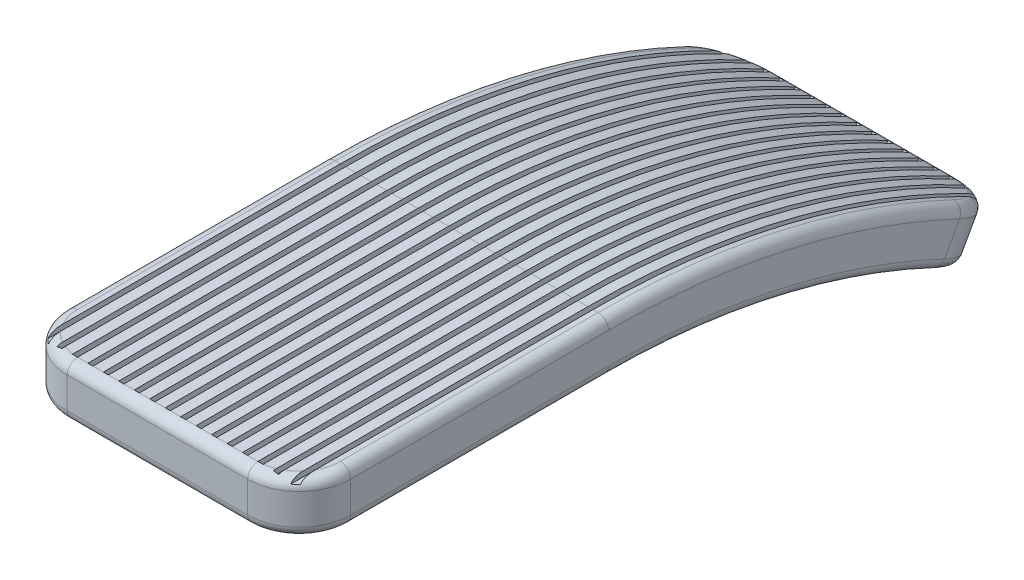
SolidWorks part; units mm, degrees
material "Silicon Rubber"
ref_plane "Front" through (0, 0, 0) normal (0, 0, 1) x (1, 0, 0)
ref_plane "Top" through (0, 0, 0) normal (0, 1, 0) x (1, 0, 0)
ref_plane "Right" through (0, 0, 0) normal (1, 0, 0) x (0, 0, -1)
sketch "Sketch1" plane through (0, 0, 0) normal (1, 0, 0) x (0, 0, -1)
  line L0 (0, 0) -> (-60, 0)
  line L1 (0, 10) -> (-60, 10)
  line L2 (-60, 10) -> (-60, 0)
  line L3 (73.1384, -18.8963) -> (77.9823, -10.1477)
  arc A0 (0, 0) -> (73.1384, -18.8963) centre (0, -150.99) cw
  arc A1 (0, 10) -> (77.9823, -10.1477) centre (0, -150.99) cw
  dimension "D1" = 150.99
  dimension "D2" = 75.54
  dimension "D3" = 60
  dimension "D4" = 10
extrude "Boss-Extrude1" add sketch "Sketch1" along normal blind 55
fillet "Fillet1" radius 10 4 edges at (0, -14.522, -75.5603) (55, -14.522, -75.5603) (0, 5, 60) (55, 5, 60)
fillet "Fillet2" radius 2 20 edges at (55, 0, 25) (52.0711, 0, 57.0711) (27.5, 0, 60) (2.9289, 0, 57.0711) (0, 0, 25) (0, -3.6292, -32.9056) (2.1865, -17.1164, -69.8271) (27.5, -18.8963, -73.1384) (51.2467, -17.8488, -71.2138) (52.8129, -8.3656, -74.6731) (27.5, -10.1477, -77.9823) (3.7533, -9.0994, -76.0582) (0, 6.0578, -35.4087) (0, 10, 25) (2.9289, 10, 57.0711) (27.5, 10, 60) (52.0711, 10, 57.0711) (55, 10, 25) (55, -3.6292, -32.9056) (55, 6.0578, -35.4087)
sketch "Sketch2" plane through (0, 0, 0) normal (1, 0, 0) x (0, 0, -1)
  line L6 (-58, 10) -> (-58, 9)
  line L7 (75.7311, -10.0588) -> (76.2044, -9.1779)
  line L8 (-50, 9) -> (-58, 9)
  line L9 (0, 9) -> (-50, 9)
  line L10 (-50, 9) -> (-58, 9)
  line L11 (0, 9) -> (-50, 9)
  line L12 (-50, 10) -> (-58, 10) construction
  line L13 (-50, 10) -> (0, 10) construction
  line L14 (-50, 10) -> (-58, 10)
  line L15 (-50, 10) -> (0, 10)
  arc A5 (76.2044, -9.1779) -> (68.9693, -5.5218) centre (0, -150.99) ccw construction
  arc A6 (75.7311, -10.0588) -> (68.5409, -6.4253) centre (0, -150.99) ccw
  arc A7 (68.5409, -6.4253) -> (0, 9) centre (0, -150.99) ccw
  arc A8 (75.7311, -10.0588) -> (68.5409, -6.4253) centre (0, -150.99) ccw
  arc A9 (68.5409, -6.4253) -> (0, 9) centre (0, -150.99) ccw
  arc A10 (68.9693, -5.5218) -> (0, 10) centre (0, -150.99) ccw construction
  arc A11 (76.2044, -9.1779) -> (68.9693, -5.5218) centre (0, -150.99) ccw
  arc A12 (68.9693, -5.5218) -> (0, 10) centre (0, -150.99) ccw
  point P2 (76.2044, -9.1779)
  point P3 (75.7311, -10.0588)
  dimension "D1" = 1
extrude "Cut-Extrude1" cut sketch "Sketch2" along normal blind 1 from offset 3 contours A11 A12 L15 L14 L6 L10 L11 A9 A8 L7
pattern_linear "LPattern1" count 17 spacing 3 along (1, 0, 0) of "Cut-Extrude1"
